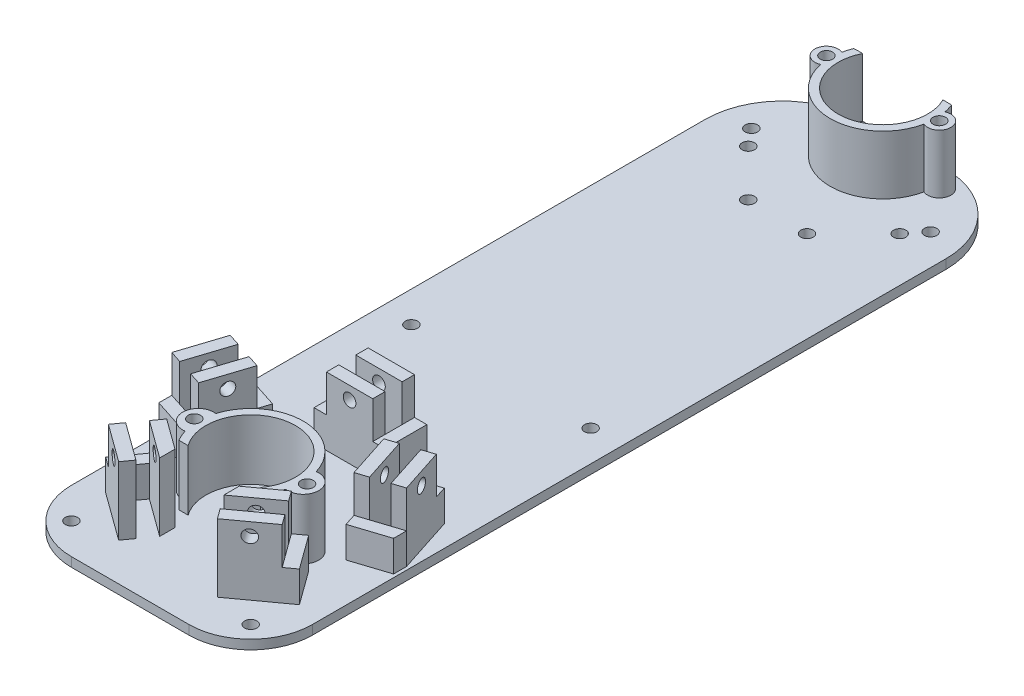
SolidWorks part; units mm, degrees
ref_plane "Ön Düzlem" through (0, 0, 0) normal (0, 0, 1) x (1, 0, 0)
ref_plane "Üst Düzlem" through (0, 0, 0) normal (0, 1, 0) x (1, 0, 0)
ref_plane "Sağ Düzlem" through (0, 0, 0) normal (1, 0, 0) x (0, 0, -1)
sketch "Çizim1" plane through (0, 0, 0) normal (0, 1, 0) x (1, 0, 0)
  line L1 (-39, -48) -> (39, -48)
  line L2 (-39, -48) -> (-39, 30)
  line L3 (-39, 30) -> (39, 30)
  line L4 (39, -48) -> (39, 30)
  line L5 (-39, -48) -> (39, 30) construction
  line L6 (-39, 30) -> (39, -48) construction
  dimension "D1" = 78
  dimension "D2" = 78
extrude "Yükseklik-Ekstrüzyon1" add sketch "Çizim1" along normal blind 3
sketch "Çizim9" plane through (0, 3, 0) normal (0, 1, 0) x (1, 0, 0)
  line L0 (-14.7224, -17.5) -> (-11.7473, -17.5)
  line L3 (11.7473, -17.5) -> (14.7224, -17.5)
  arc A0 (11.7473, -17.5) -> (-11.7473, -17.5) centre (0, -9) ccw
  arc A1 (-16.2647, -13.9456) -> (-14.7224, -17.5) centre (0, -9) ccw
  arc A2 (-16.2647, -4.0544) -> (-16.2647, -13.9456) centre (-17, -9) ccw
  arc A3 (16.2647, -13.9456) -> (16.2647, -4.0544) centre (17, -9) ccw
  arc A4 (16.2647, -4.0544) -> (-16.2647, -4.0544) centre (0, -9) ccw
  arc A5 (14.7224, -17.5) -> (16.2647, -13.9456) centre (0, -9) ccw
  dimension "D1" = 5
  dimension "D2" = 14.5
  dimension "D3" = 17
extrude "Yükseklik-Ekstrüzyon5" add sketch "Çizim9" along normal blind 19.5
sketch "Çizim10" plane through (0, 22.5, 0) normal (0, 1, 0) x (1, 0, 0)
  circle A2 centre (-18.25, -9) radius 2
  circle A5 centre (18.25, -9) radius 2
  dimension "D1" = 36.5
extrude "Kes-Ekstrüzyon3" cut sketch "Çizim10" against normal blind 26.5
sketch "Çizim18" plane through (0, 0, 0) normal (0, 1, 0) x (1, 0, 0)
  line L0 (-39, 30) -> (-39, 108)
  line L1 (-39, 108) -> (39, 108)
  line L2 (39, 108) -> (39, 30)
  line L3 (39, 30) -> (-39, 30)
extrude "Yükseklik-Ekstrüzyon8" add sketch "Çizim18" along normal blind 3
sketch "dik" plane through (0, 3, 0) normal (0, 1, 0) x (1, 0, 0)
  line L1 (-7.5, 36.5) -> (7.5, 36.5)
  line L4 (-7.5, 27) -> (-7.5, 23)
  line L5 (7.5, 36.5) -> (7.5, 32.5)
  line L6 (7.5, 32.5) -> (-7.5, 32.5)
  line L7 (-7.5, 32.5) -> (-7.5, 36.5)
  line L8 (-7.5, 23) -> (7.5, 23)
  line L9 (7.5, 23) -> (7.5, 27)
  line L10 (7.5, 27) -> (-7.5, 27)
  line L33 (33.347, 17.7211) -> (37.9822, 3.4552)
  line L34 (24.312, 14.7854) -> (20.5077, 13.5493)
  line L35 (37.9822, 3.4552) -> (34.178, 2.2191)
  line L36 (34.178, 2.2191) -> (29.5428, 16.485)
  line L37 (29.5428, 16.485) -> (33.347, 17.7211)
  line L38 (20.5077, 13.5493) -> (25.143, -0.7165)
  line L39 (25.143, -0.7165) -> (28.9472, 0.5196)
  line L40 (28.9472, 0.5196) -> (24.312, 14.7854)
  line L41 (28.1096, -26.9297) -> (15.9743, -35.7465)
  line L42 (22.5256, -19.2441) -> (20.1745, -16.008)
  line L43 (15.9743, -35.7465) -> (13.6232, -32.5105)
  line L44 (13.6232, -32.5105) -> (25.7584, -23.6937)
  line L45 (25.7584, -23.6937) -> (28.1096, -26.9297)
  line L46 (20.1745, -16.008) -> (10.3904, -23.1166)
  line L48 (10.3904, -28.0609) -> (22.5256, -19.2441)
  line L49 (-15.9743, -35.7465) -> (-28.1096, -26.9297)
  line L51 (-28.1096, -26.9297) -> (-25.7584, -23.6937)
  line L52 (-25.7584, -23.6937) -> (-13.6232, -32.5105)
  line L53 (-13.6232, -32.5105) -> (-15.9743, -35.7465)
  line L54 (-10.3904, -23.1166) -> (-20.1745, -16.008)
  line L55 (-20.1745, -16.008) -> (-22.5256, -19.2441)
  line L56 (-22.5256, -19.2441) -> (-10.3904, -28.0609)
  line L57 (-37.9822, 3.4552) -> (-33.347, 17.7211)
  line L58 (-28.9472, 0.5196) -> (-25.143, -0.7165)
  line L59 (-33.347, 17.7211) -> (-29.5428, 16.485)
  line L60 (-29.5428, 16.485) -> (-34.178, 2.2191)
  line L61 (-34.178, 2.2191) -> (-37.9822, 3.4552)
  line L62 (-25.143, -0.7165) -> (-20.5077, 13.5493)
  line L63 (-20.5077, 13.5493) -> (-24.312, 14.7854)
  line L64 (-24.312, 14.7854) -> (-28.9472, 0.5196)
  line L65 (-10.3904, -28.0609) -> (-10.3904, -23.1166)
  line L66 (10.3904, -28.0609) -> (10.3904, -23.1166)
  line L68 (-10.3904, -28.0609) -> (-8.0392, -24.8248) [skipped]
  line L69 (8.0392, -24.8248) -> (10.3904, -28.0609) [skipped]
  dimension "D1" = 5
sketch "yandestek" plane through (0, 3, 0) normal (0, 1, 0) x (1, 0, 0)
  line L0 (-7.5, 36.5) -> (-7.5, 23)
  line L1 (-7.5, 23) -> (-11.5, 23)
  line L2 (-11.5, 23) -> (-11.5, 36.5)
  line L3 (-11.5, 36.5) -> (-7.5, 36.5)
  line L4 (7.5, 36.5) -> (11.5, 36.5)
  line L5 (11.5, 36.5) -> (11.5, 23)
  line L6 (11.5, 23) -> (7.5, 23)
  line L7 (7.5, 23) -> (7.5, 36.5)
  line L8 (0, 5.5) -> (0, -1)
  line L33 (33.347, 17.7211) -> (20.5077, 13.5493)
  line L34 (20.5077, 13.5493) -> (19.2717, 17.3536)
  line L35 (19.2717, 17.3536) -> (32.1109, 21.5253)
  line L36 (32.1109, 21.5253) -> (33.347, 17.7211)
  line L38 (37.9822, -0.7506) -> (26.3791, -4.5207)
  line L39 (26.3791, -4.5207) -> (25.143, -0.7165)
  line L40 (25.143, -0.7165) -> (37.9822, 3.4552)
  line L41 (28.1096, -26.9297) -> (20.1745, -16.008)
  line L42 (20.1745, -16.008) -> (23.4105, -13.6569)
  line L43 (23.4105, -13.6569) -> (31.3456, -24.5786)
  line L44 (31.3456, -24.5786) -> (28.1096, -26.9297)
  line L53 (-28.1096, -26.9297) -> (-31.3456, -24.5786)
  line L54 (-31.3456, -24.5786) -> (-23.4105, -13.6569)
  line L55 (-23.4105, -13.6569) -> (-20.1745, -16.008)
  line L56 (-20.1745, -16.008) -> (-28.1096, -26.9297)
  line L57 (-37.9822, 3.4552) -> (-25.143, -0.7165)
  line L58 (-25.143, -0.7165) -> (-26.3791, -4.5207)
  line L59 (-26.3791, -4.5207) -> (-37.9822, -0.7506)
  line L61 (-33.347, 17.7211) -> (-32.1109, 21.5253)
  line L62 (-32.1109, 21.5253) -> (-19.2717, 17.3536)
  line L63 (-19.2717, 17.3536) -> (-20.5077, 13.5493)
  line L64 (-20.5077, 13.5493) -> (-33.347, 17.7211)
  line L65 (-37.9822, 3.4552) -> (-37.9822, -0.7506)
  line L66 (37.9822, 3.4552) -> (37.9822, -0.7506)
  line L68 (37.9822, 3.4552) -> (39.2183, -0.349) [skipped]
  line L69 (-39.2183, -0.349) -> (-37.9822, 3.4552) [skipped]
  line L70 (15.9743, -35.7465) -> (12.7383, -38.0977) [skipped]
  line L71 (12.7383, -38.0977) -> (4.8032, -27.1759) [skipped]
  line L72 (4.8032, -27.1759) -> (8.0392, -24.8248) [skipped]
  line L73 (8.0392, -24.8248) -> (15.9743, -35.7465) [skipped]
  line L74 (-15.9743, -35.7465) -> (-8.0392, -24.8248) [skipped]
  line L75 (-8.0392, -24.8248) -> (-4.8032, -27.1759) [skipped]
  line L76 (-4.8032, -27.1759) -> (-12.7383, -38.0977) [skipped]
  line L77 (-12.7383, -38.0977) -> (-15.9743, -35.7465) [skipped]
  arc A2 (11.7473, -17.5) -> (-11.7473, -17.5) centre (0, -9) ccw construction
  dimension "D1" = 5
extrude "Yükseklik-Ekstrüzyon12" add sketch "dik" along normal blind 22
extrude "Yükseklik-Ekstrüzyon13" add sketch "yandestek" along normal blind 10 contours L57 L65 L59 L58 | L56 L55 L54 L53 | L64 L63 L62 L61 | L3 L2 L1 L0 | L7 L6 L5 L4 | L36 L35 L34 L33 | L66 L40 L39 L38 | L44 L43 L42 L41
sketch "Çizim23" plane through (-22.5175, 0, 30.9926) normal (-0.5878, 0, 0.809) x (0.809, 0, 0.5878)
  circle A0 centre (0.5878, 20.9) radius 2.05
extrude "Kes-Ekstrüzyon4" cut sketch "Çizim23" against normal blind 14
sketch "Çizim24" plane through (22.5175, 0, 30.9926) normal (0.5878, 0, 0.809) x (0.809, 0, -0.5878)
  circle A0 centre (-0.5878, 20.9) radius 2.05
extrude "Kes-Ekstrüzyon5" cut sketch "Çizim24" against normal blind 14
sketch "Çizim25" plane through (35.3707, 0, -11.4926) normal (0.9511, 0, -0.309) x (-0.309, 0, -0.9511)
  circle A0 centre (-0.9511, 20.9) radius 2.05
extrude "Kes-Ekstrüzyon6" cut sketch "Çizim25" against normal blind 14
sketch "Çizim26" plane through (0, 0, -36.5) normal (0, 0, -1) x (-1, 0, 0)
  circle A0 centre (0, 20.9) radius 2.05
extrude "Kes-Ekstrüzyon7" cut sketch "Çizim26" against normal blind 14
sketch "Çizim27" plane through (-35.3707, 0, -11.4926) normal (-0.9511, 0, -0.309) x (-0.309, 0, 0.9511)
  circle A0 centre (0.9511, 20.9) radius 2.05
extrude "Kes-Ekstrüzyon8" cut sketch "Çizim27" against normal blind 14
sketch "Çizim28" plane through (0, 3, 0) normal (0, 1, 0) x (1, 0, 0)
  line L0 (-39, 108) -> (-39, 202)
  line L1 (-39, 202) -> (39, 202)
  line L2 (39, 202) -> (39, 108)
  line L3 (39, 108) -> (-39, 108)
extrude "Yükseklik-Ekstrüzyon15" add sketch "Çizim28" against normal blind 3
sketch "Çizim29" plane through (0, 3, 0) normal (0, 1, 0) x (1, 0, 0)
  circle A0 centre (-9.5, 161.5) radius 2
  circle A1 centre (9.5, 161.5) radius 2
  circle A4 centre (-24.5, 176.5) radius 2
  circle A5 centre (24.5, 176.5) radius 2
extrude "Kes-Ekstrüzyon9" cut sketch "Çizim29" against normal blind 3
sketch "Çizim30" plane through (0, 3, 0) normal (0, 1, 0) x (1, 0, 0)
  line L1 (-15.7829, 202) -> (-12.9864, 202)
  line L3 (39, 202) -> (-39, 202) construction
  line L4 (12.9864, 202) -> (15.7829, 202)
  arc A2 (-15.7829, 202) -> (-16.7042, 198.9666) centre (0, 195.55) ccw
  arc A3 (-12.9864, 202) -> (12.9864, 202) centre (0, 195.55) ccw
  arc A4 (-16.7042, 198.9666) -> (-16.7042, 192.1334) centre (-18.25, 195.55) ccw
  arc A5 (16.7042, 192.1334) -> (16.7042, 198.9666) centre (18.25, 195.55) ccw
  arc A6 (-16.7042, 192.1334) -> (16.7042, 192.1334) centre (0, 195.55) ccw
  arc A7 (16.7042, 198.9666) -> (15.7829, 202) centre (0, 195.55) ccw
  circle A8 centre (-18.25, 195.55) radius 2
  circle A9 centre (18.25, 195.55) radius 2
extrude "Yükseklik-Ekstrüzyon16" add sketch "Çizim30" along normal blind 19
sketch "Çizim31" plane through (0, 3, 0) normal (0, 1, 0) x (1, 0, 0)
  circle A0 centre (0, -9) radius 7.5
  circle A1 centre (0, 195.55) radius 7.5
extrude "Kes-Ekstrüzyon10" cut sketch "Çizim31" against normal blind 19
sketch "Çizim32" plane through (0, 3, 0) normal (0, 1, 0) x (1, 0, 0)
  circle A0 centre (-29, 182) radius 2
  circle A1 centre (29, 182) radius 2
  circle A2 centre (-18.25, 195.55) radius 2
  circle A3 centre (18.25, 195.55) radius 2
  circle A5 centre (-29, -38) radius 2
  circle A6 centre (29, -38) radius 2
  circle A7 centre (-29, 72) radius 2
  circle A8 centre (29, 72) radius 2
extrude "Kes-Ekstrüzyon11" cut sketch "Çizim32" against normal blind 19
fillet "Radyus1" radius 25 2 edges at (-39, 1.5, -202) (39, 1.5, -202)
fillet "Radyus2" radius 20 2 edges at (39, 1.5, 48) (-39, 1.5, 48)
